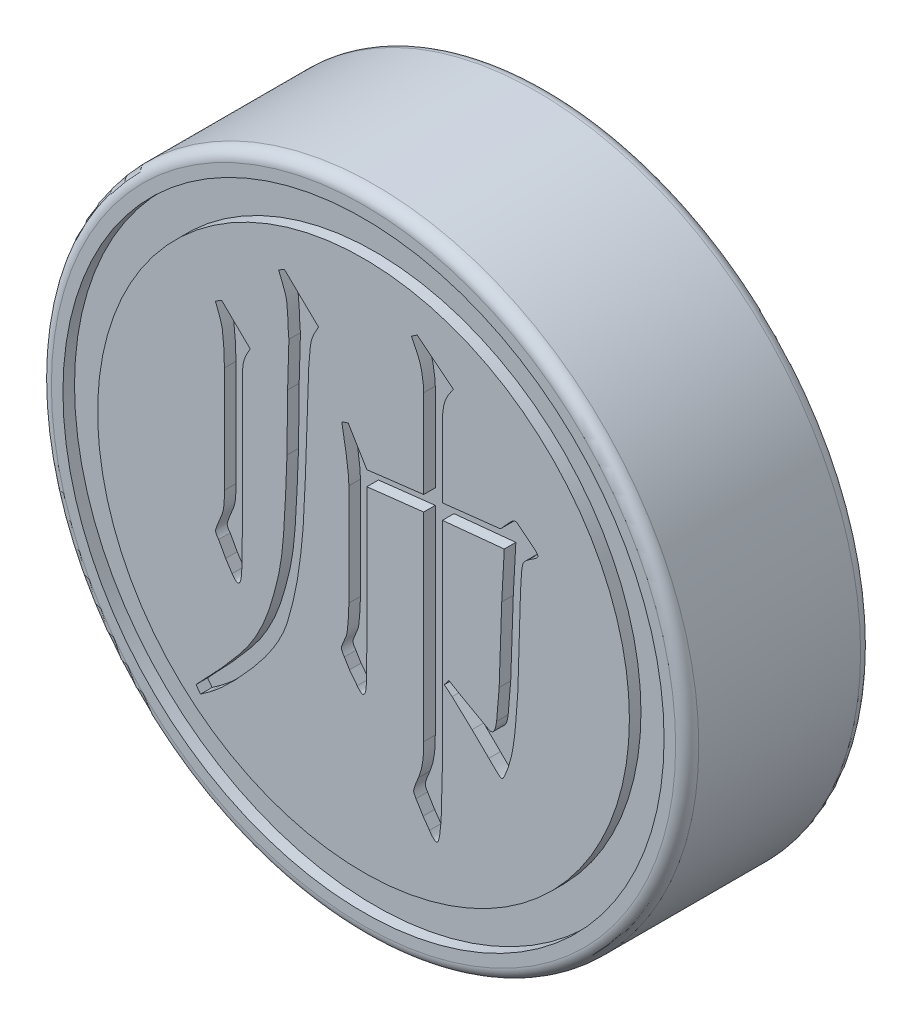
SolidWorks part; units mm, degrees
ref_plane "前视基准面" through (0, 0, 0) normal (0, 0, 1) x (1, 0, 0)
ref_plane "上视基准面" through (0, 0, 0) normal (0, 1, 0) x (1, 0, 0)
ref_plane "右视基准面" through (0, 0, 0) normal (1, 0, 0) x (0, 0, -1)
sketch "草图1" plane through (0, 0, 0) normal (0, 0, 1) x (1, 0, 0)
  circle A0 centre (0, 0) radius 14
extrude "凸台-拉伸1" add sketch "草图1" along normal blind 8
sketch "草图2" plane through (0, 0, 8) normal (0, 0, 1) x (1, 0, 0)
  circle A0 centre (0, 0) radius 13
  circle A1 centre (0, 0) radius 11.5
extrude "切除-拉伸1" cut sketch "草图2" against normal blind 0.5
sketch "草图3" plane through (0, 0, 0) normal (0, 0, -1) x (-1, 0, 0)
  circle A0 centre (0, 0) radius 5.1
extrude "切除-拉伸2" cut sketch "草图3" against normal blind 5
chamfer "倒角1" distance 0.5 angle 45 1 edges at (-5.1, 0, 0)
fillet "圆角1" radius 0.5 2 edges at (14, 0, 8) (14, 0, 0)
sketch "草图4" plane through (0, 0, 8) normal (0, 0, 1) x (1, 0, 0)
  text T0 "帅" font "汉仪长仿宋体" height 13
extrude "切除-拉伸3" cut sketch "草图4" against normal blind 0.5
